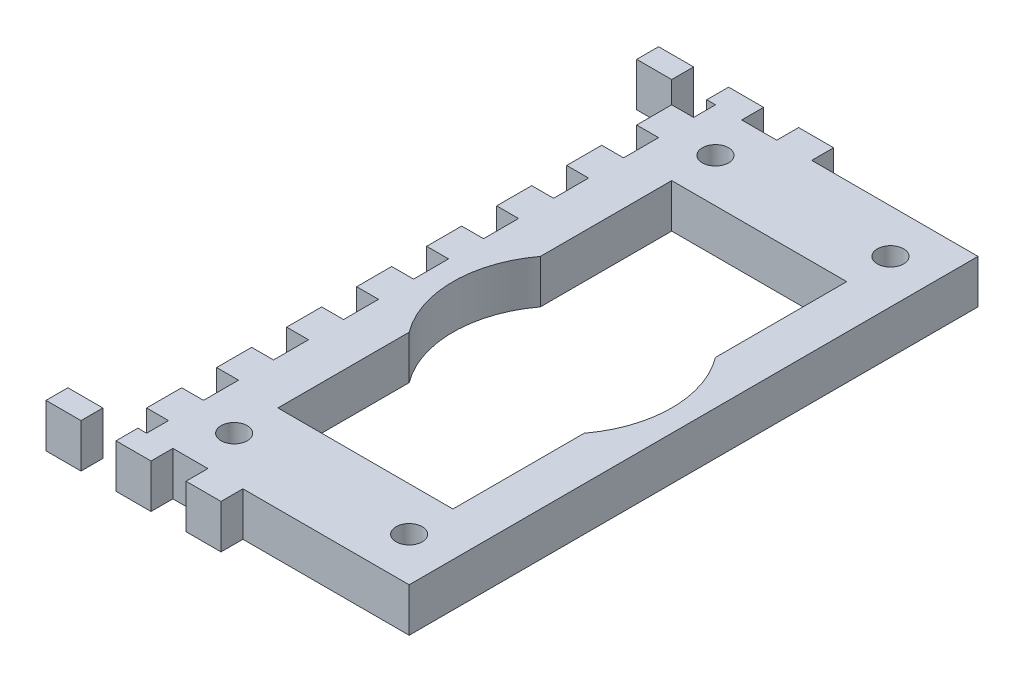
SolidWorks part; units mm, degrees
ref_plane "Front Plane" through (0, 0, 0) normal (0, 0, 1) x (1, 0, 0)
ref_plane "Top Plane" through (0, 0, 0) normal (0, 1, 0) x (1, 0, 0)
ref_plane "Right Plane" through (0, 0, 0) normal (1, 0, 0) x (0, 0, -1)
sketch "Sketch1" plane through (0, 0, 0) normal (0, 1, 0) x (1, 0, 0)
  line L1 (-19.05, -41.275) -> (19.05, -41.275)
  line L2 (-19.05, -41.275) -> (-19.05, 41.275)
  line L3 (-19.05, 41.275) -> (19.05, 41.275)
  line L4 (19.05, -41.275) -> (19.05, 41.275)
  line L5 (-19.05, -41.275) -> (19.05, 41.275) construction
  line L6 (-19.05, 41.275) -> (19.05, -41.275) construction
  line L7 (-12.7, -28.575) -> (12.7, -28.575)
  line L8 (-12.7, -28.575) -> (-12.7, 28.575)
  line L9 (-12.7, 28.575) -> (12.7, 28.575)
  line L10 (12.7, -28.575) -> (12.7, 28.575)
  line L11 (-12.7, -28.575) -> (12.7, 28.575) construction
  line L12 (-12.7, 28.575) -> (12.7, -28.575) construction
  circle A0 centre (-12.7, 34.925) radius 1.905
  circle A1 centre (12.7, 34.925) radius 1.905
  circle A2 centre (12.7, -34.925) radius 1.905
  circle A3 centre (-12.7, -34.925) radius 1.905
  point P0 (0, 0)
  point P5 (0, 0)
  dimension "D3" = 28.575
  dimension "D5" = 3.81
  dimension "D1" = 38.1
  dimension "D2" = 82.55
  dimension "D4" = 12.7
  dimension "D6" = 6.35
  dimension "D7" = 34.925
  dimension "D10" = 25.4
  dimension "D11" = 69.85
  dimension "D8" = 2
  dimension "D9" = 2
extrude "Boss-Extrude1" add sketch "Sketch1" along normal blind 6.35
sketch "Sketch2" plane through (0, 0, 0) normal (0, 1, 0) x (1, 0, 0)
  circle A0 centre (0, 0) radius 15.875
  dimension "D1" = 31.75
extrude "Cut-Extrude1" cut sketch "Sketch2" along normal through all
sketch "Sketch3" plane through (0, 6.35, 0) normal (0, 1, 0) x (1, 0, 0)
  line L0 (-19.05, 41.275) -> (-19.05, -41.275) construction
  line L1 (-19.05, 38.1) -> (-22.225, 38.1)
  line L2 (-19.05, 38.1) -> (-19.05, 33.02)
  line L3 (-19.05, 33.02) -> (-22.225, 33.02)
  line L4 (-22.225, 38.1) -> (-22.225, 33.02)
  line L5 (-19.05, 44.45) -> (-22.225, 44.45) construction
  line L6 (-19.05, 27.94) -> (-19.05, 22.86)
  line L7 (-19.05, 27.94) -> (-22.225, 27.94)
  line L8 (-22.225, 27.94) -> (-22.225, 22.86)
  line L9 (-19.05, 22.86) -> (-22.225, 22.86)
  line L10 (-19.05, 17.78) -> (-19.05, 12.7)
  line L11 (-19.05, 17.78) -> (-22.225, 17.78)
  line L12 (-22.225, 17.78) -> (-22.225, 12.7)
  line L13 (-19.05, 12.7) -> (-22.225, 12.7)
  line L14 (-19.05, 7.62) -> (-19.05, 2.54)
  line L15 (-19.05, 7.62) -> (-22.225, 7.62)
  line L16 (-22.225, 7.62) -> (-22.225, 2.54)
  line L17 (-19.05, 2.54) -> (-22.225, 2.54)
  line L18 (-19.05, -2.54) -> (-19.05, -7.62)
  line L19 (-19.05, -2.54) -> (-22.225, -2.54)
  line L20 (-22.225, -2.54) -> (-22.225, -7.62)
  line L21 (-19.05, -7.62) -> (-22.225, -7.62)
  line L22 (-19.05, -12.7) -> (-19.05, -17.78)
  line L23 (-19.05, -12.7) -> (-22.225, -12.7)
  line L24 (-22.225, -12.7) -> (-22.225, -17.78)
  line L25 (-19.05, -17.78) -> (-22.225, -17.78)
  line L26 (-19.05, -22.86) -> (-19.05, -27.94)
  line L27 (-19.05, -22.86) -> (-22.225, -22.86)
  line L28 (-22.225, -22.86) -> (-22.225, -27.94)
  line L29 (-19.05, -27.94) -> (-22.225, -27.94)
  line L30 (-19.05, -33.02) -> (-19.05, -38.1)
  line L31 (-19.05, -33.02) -> (-22.225, -33.02)
  line L32 (-22.225, -33.02) -> (-22.225, -38.1)
  line L33 (-19.05, -38.1) -> (-22.225, -38.1)
  line L34 (19.05, 41.275) -> (-19.05, 41.275) construction
  line L35 (-5.08, 41.275) -> (-10.16, 41.275)
  line L36 (-5.08, 41.275) -> (-5.08, 44.45)
  line L37 (-5.08, 44.45) -> (-10.16, 44.45)
  line L38 (-10.16, 41.275) -> (-10.16, 44.45)
  line L39 (0, 44.45) -> (-4.953, 44.45) construction
  line L40 (0, 41.275) -> (0, 44.45) construction
  line L41 (-15.24, 41.275) -> (-20.32, 41.275)
  line L42 (-15.24, 41.275) -> (-15.24, 44.45)
  line L43 (-15.24, 44.45) -> (-20.32, 44.45)
  line L44 (-20.32, 41.275) -> (-20.32, 44.45)
  line L45 (-25.4, 41.275) -> (-30.48, 41.275)
  line L46 (-25.4, 41.275) -> (-25.4, 44.45)
  line L47 (-25.4, 44.45) -> (-30.48, 44.45)
  line L48 (-30.48, 41.275) -> (-30.48, 44.45)
  line L49 (0, 0) -> (5.7808, 0) construction
  line L50 (-25.4, -41.275) -> (-30.48, -41.275)
  line L51 (-25.4, -41.275) -> (-25.4, -44.45)
  line L52 (-25.4, -44.45) -> (-30.48, -44.45)
  line L53 (-30.48, -41.275) -> (-30.48, -44.45)
  line L54 (-15.24, -41.275) -> (-20.32, -41.275)
  line L55 (-15.24, -41.275) -> (-15.24, -44.45)
  line L56 (-15.24, -44.45) -> (-20.32, -44.45)
  line L57 (-20.32, -41.275) -> (-20.32, -44.45)
  line L58 (-5.08, -41.275) -> (-10.16, -41.275)
  line L59 (-5.08, -41.275) -> (-5.08, -44.45)
  line L60 (-5.08, -44.45) -> (-10.16, -44.45)
  line L61 (-10.16, -41.275) -> (-10.16, -44.45)
  dimension "D1" = 5.08
  dimension "D2" = 3.175
  dimension "D3" = 6.35
  dimension "D5" = 5.08
  dimension "D4" = 8
  dimension "D6" = 3
extrude "Boss-Extrude2" add sketch "Sketch3" against normal blind 6.35
